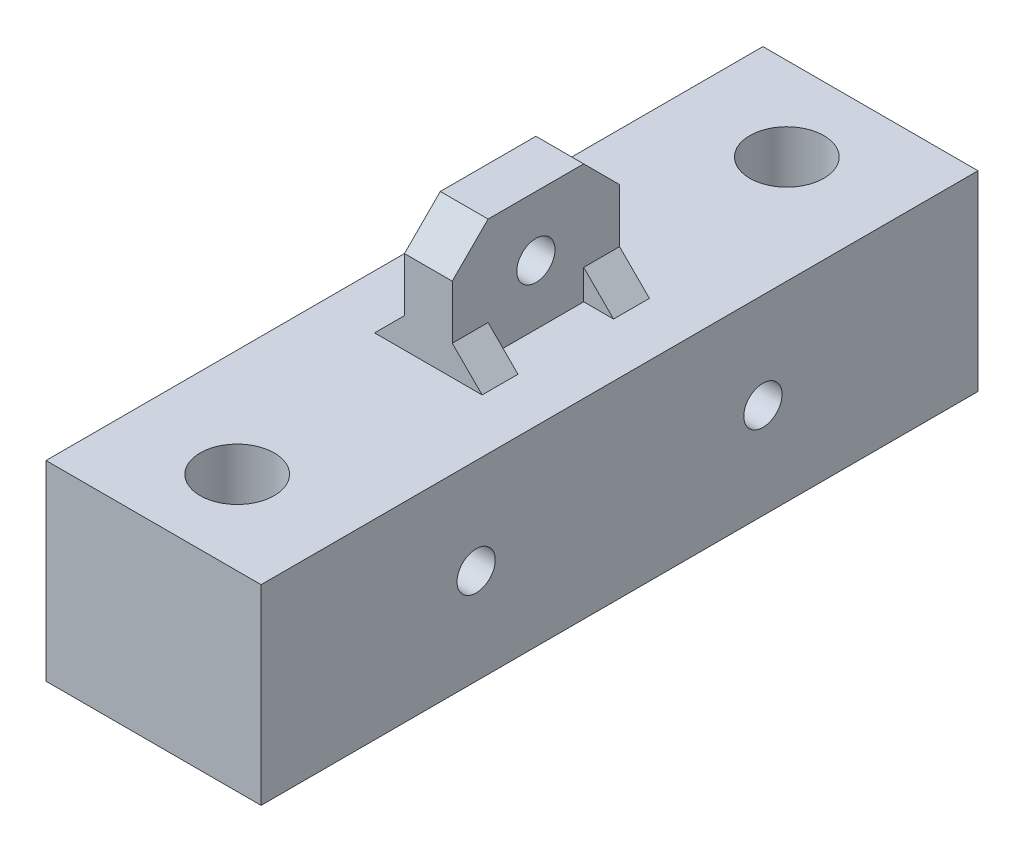
SolidWorks part; units mm, degrees
material "PLA+"
ref_plane "Front Plane" through (0, 0, 0) normal (0, 0, 1) x (1, 0, 0)
ref_plane "Top Plane" through (0, 0, 0) normal (0, 1, 0) x (1, 0, 0)
ref_plane "Right Plane" through (0, 0, 0) normal (1, 0, 0) x (0, 0, -1)
sketch "Sketch1" plane through (0, 0, 0) normal (0, 1, 0) x (1, 0, 0)
  line L1 (-9, -30) -> (9, -30)
  line L2 (-9, -30) -> (-9, 30)
  line L3 (-9, 30) -> (9, 30)
  line L4 (9, -30) -> (9, 30)
  line L5 (-9, -30) -> (9, 30) construction
  line L6 (-9, 30) -> (9, -30) construction
  point P0 (0, 0)
  dimension "D1" = 18
  dimension "D2" = 60
extrude "Boss-Extrude1" add sketch "Sketch1" along normal blind 16
sketch "Sketch2" plane through (0, 16, 0) normal (0, 1, 0) x (1, 0, 0)
  line L0 (9, 30) -> (-9, 30) construction
  line L1 (-9, -30) -> (9, -30) construction
  circle A0 centre (0, 23) radius 3.1
  circle A1 centre (0, -23) radius 3.1
  dimension "D1" = 6.2
  dimension "D2" = 6.2
  dimension "D3" = 7
  dimension "D4" = 7
extrude "Cut-Extrude1" cut sketch "Sketch2" against normal through all
sketch "Sketch3" plane through (-9, 0, 0) normal (-1, 0, 0) x (0, 0, 1)
  line L0 (-30, 0) -> (30, 0) construction
  line L1 (-30, 16) -> (-30, 0) construction
  line L3 (30, 16) -> (30, 0) construction
  circle A0 centre (-12, 8) radius 1.6
  circle A1 centre (12, 8) radius 1.6
  dimension "D3" = 3.2
  dimension "D4" = 3.2
  dimension "D5" = 18
  dimension "D1" = 8
  dimension "D2" = 18
extrude "Cut-Extrude2" cut sketch "Sketch3" against normal through all
sketch "Sketch4" plane through (0, 16, 0) normal (0, 1, 0) x (1, 0, 0)
  line L1 (-2, -7) -> (2, -7)
  line L2 (-2, -7) -> (-2, 7)
  line L3 (-2, 7) -> (2, 7)
  line L4 (2, -7) -> (2, 7)
  line L5 (-2, -7) -> (2, 7) construction
  line L6 (-2, 7) -> (2, -7) construction
  point P0 (0, 0)
  dimension "D1" = 14
  dimension "D2" = 4
extrude "Boss-Extrude2" add sketch "Sketch4" along normal blind 10 contours L3 L4 L1 L2
sketch "Sketch5" plane through (-2, 0, 0) normal (-1, 0, 0) x (0, 0, 1)
  line L0 (7, 26) -> (-7, 26) construction
  circle A0 centre (0, 21) radius 1.6
  dimension "D1" = 3.2
  dimension "D2" = 5
extrude "Cut-Extrude3" cut sketch "Sketch5" against normal through all
chamfer "Chamfer1" distance 3 angle 45 2 edges at (0, 26, -7) (0, 26, 7)
sketch "Sketch6" plane through (0, 0, 7) normal (0, 0, 1) x (1, 0, 0)
  line L0 (-2, 18.5) -> (-4.5, 16)
  line L1 (-2, 23) -> (-2, 16) construction
  line L2 (-9, 16) -> (9, 16) construction
  line L3 (-4.5, 16) -> (-2, 16)
  line L4 (-2, 16) -> (-2, 18.5)
  line L5 (2, 18.5) -> (4.5, 16)
  line L6 (2, 23) -> (2, 16) construction
  line L7 (4.5, 16) -> (2, 16)
  line L8 (2, 16) -> (2, 18.5)
  dimension "D1" = 2.5
  dimension "D2" = 2.5
  dimension "D3" = 2.5
  dimension "D4" = 2.5
extrude "Boss-Extrude3" add sketch "Sketch6" against normal blind 3
sketch "Sketch7" plane through (0, 0, -7) normal (0, 0, -1) x (-1, 0, 0)
  line L3 (2, 18.5) -> (2, 16)
  line L4 (2, 16) -> (4.5, 16)
  line L5 (4.5, 16) -> (2, 18.5)
  line L6 (2, 18.5) -> (2, 16)
  line L7 (2, 16) -> (4.5, 16)
  line L8 (4.5, 16) -> (2, 18.5)
  line L9 (-2, 16) -> (-2, 18.5)
  line L10 (-2, 18.5) -> (-4.5, 16)
  line L11 (-4.5, 16) -> (-2, 16)
  line L12 (-2, 16) -> (-2, 18.5)
  line L13 (-2, 18.5) -> (-4.5, 16)
  line L14 (-4.5, 16) -> (-2, 16)
  dimension "D1" = 0
  dimension "D2" = 0
extrude "Boss-Extrude4" add sketch "Sketch7" against normal blind 3
